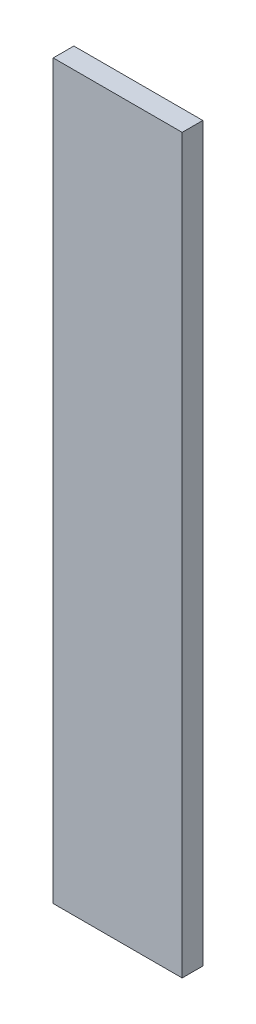
SolidWorks part; units mm, degrees
ref_plane "Front" through (0, 0, 0) normal (0, 0, 1) x (1, 0, 0)
ref_plane "Top" through (0, 0, 0) normal (0, 1, 0) x (1, 0, 0)
ref_plane "Right" through (0, 0, 0) normal (1, 0, 0) x (0, 0, -1)
sketch "Esquisse1" plane through (0, 0, 0) normal (0, 0, 1) x (1, 0, 0)
  line L1 (0, 0) -> (50, 0)
  line L2 (0, 0) -> (0, 284)
  line L3 (0, 284) -> (50, 284)
  line L4 (50, 0) -> (50, 284)
  dimension "D1" = 50
  dimension "D2" = 284
extrude "Boss.-Extru.1" add sketch "Esquisse1" along normal blind 8
